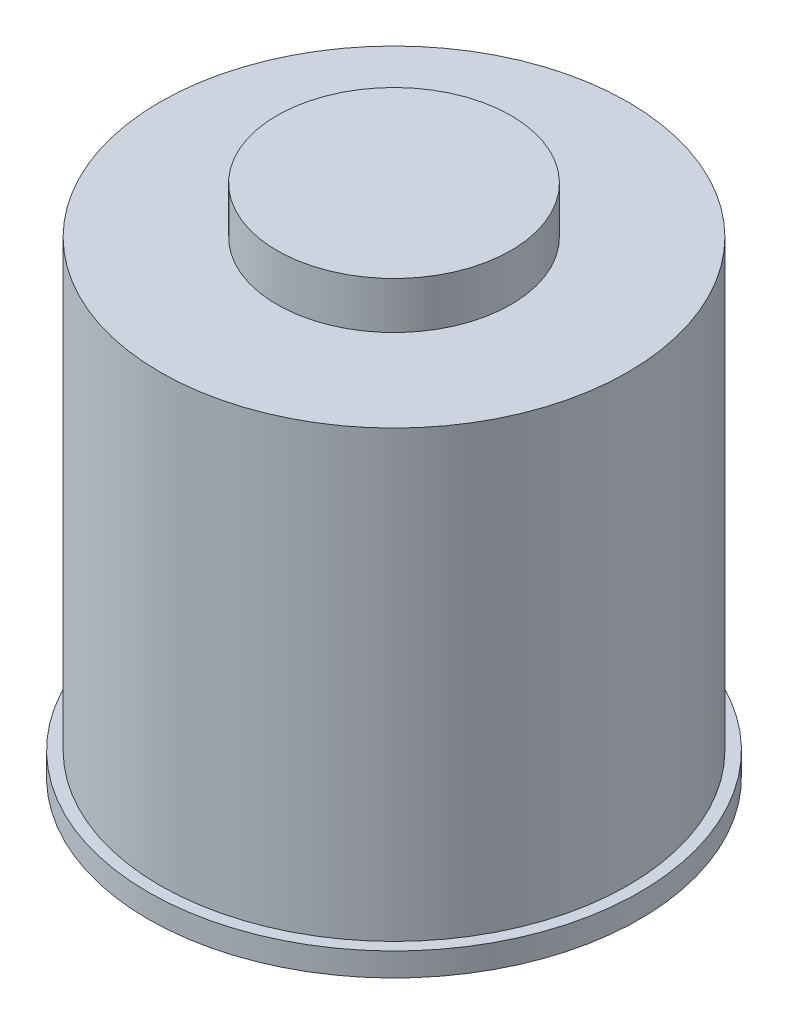
SolidWorks part; units mm, degrees
ref_plane "Plan de face" through (0, 0, 0) normal (0, 0, 1) x (1, 0, 0)
ref_plane "Plan de dessus" through (0, 0, 0) normal (0, 1, 0) x (1, 0, 0)
ref_plane "Plan de droite" through (0, 0, 0) normal (1, 0, 0) x (0, 0, -1)
sketch "Esquisse1" plane through (0, 0, 0) normal (1, 0, 0) x (0, 0, -1)
  line L0 (10.5, 0) -> (3, 0)
  line L1 (0, -3) -> (0, 0)
  line L2 (0, 0) -> (0, 20)
  line L3 (0, 20) -> (10, 20) construction
  line L4 (10, 0) -> (10, 20) construction
  line L5 (10.5, 0) -> (10.5, 1)
  line L6 (10.5, 1) -> (10, 1)
  line L7 (10, 1) -> (10, 20)
  line L8 (0, 20) -> (0, 22)
  line L9 (0, 22) -> (5, 22)
  line L10 (5, 22) -> (5, 20)
  line L11 (5, 20) -> (10, 20)
  arc A0 (3, 0) -> (0, -3) centre (0, 0) cw
  dimension "D1" = 10
  dimension "D2" = 20
  dimension "D3" = 2
  dimension "D4" = 1
  dimension "D5" = 7.5
  dimension "D6" = 5
revolve "Révolution1" add sketch "Esquisse1" angle 360 about L2
